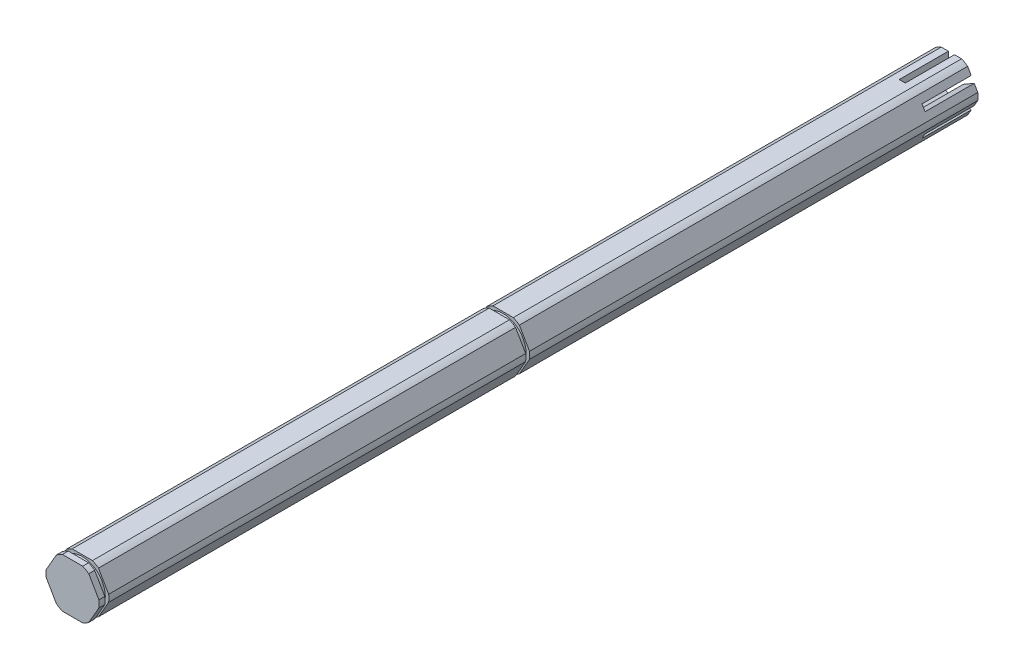
SolidWorks part; units mm, degrees
material "6061-T6 (SS)"
ref_plane "Front Plane" through (0, 0, 0) normal (0, 0, 1) x (1, 0, 0)
ref_plane "Top Plane" through (0, 0, 0) normal (0, 1, 0) x (1, 0, 0)
ref_plane "Right Plane" through (0, 0, 0) normal (1, 0, 0) x (0, 0, -1)
sketch "Sketch1" plane through (0, 0, 0) normal (1, 0, 0) x (0, 0, -1)
  line L0 (0, 0) -> (127, 0) construction
  line L1 (111.252, 7.62) -> (112.776, 7.62)
  line L2 (0, 0) -> (112.776, 0)
  line L3 (0, 0) -> (0, 7.62)
  line L4 (0, 7.62) -> (1.524, 7.62)
  line L5 (112.776, 0) -> (112.776, 7.62)
  line L7 (1.524, 7.62) -> (1.524, 5.9436)
  line L8 (1.524, 5.9436) -> (2.5146, 5.9436)
  line L9 (2.5146, 7.62) -> (2.5146, 5.9436)
  line L10 (110.2614, 5.9436) -> (111.252, 5.9436)
  line L11 (110.2614, 5.9436) -> (110.2614, 7.62)
  line L12 (2.5146, 7.62) -> (110.2614, 7.62)
  line L13 (111.252, 5.9436) -> (111.252, 7.62)
  dimension "D1" = 127
  dimension "D2" = 107.7468
  dimension "D3" = 7.62
  dimension "D4" = 0.9906
  dimension "D5" = 11.8872
  dimension "D6" = 1.524
  dimension "D8" = 1.524
revolve "Revolve3" add sketch "Sketch1" angle 360 about L0
sketch "Sketch2" plane through (0, 0, -112.776) normal (0, 0, -1) x (-1, 0, 0)
  line L1 (6.8111, 0.9028) -> (4.1874, 5.4472)
  line L2 (2.6237, 6.35) -> (-2.6237, 6.35)
  line L3 (-4.1874, 5.4472) -> (-6.8111, 0.9028)
  line L4 (-6.8111, -0.9028) -> (-4.1874, -5.4472)
  line L5 (-2.6237, -6.35) -> (2.6237, -6.35)
  line L6 (4.1874, -5.4472) -> (6.8111, -0.9028)
  circle A0 centre (0, 0) radius 6.35 construction
  arc A1 (-2.6237, 6.35) -> (-4.1874, 5.4472) centre (0, 0) ccw
  arc A2 (2.6237, -6.35) -> (4.1874, -5.4472) centre (0, 0) ccw
  arc A3 (-4.1874, -5.4472) -> (-2.6237, -6.35) centre (0, 0) ccw
  arc A4 (4.1874, 5.4472) -> (2.6237, 6.35) centre (0, 0) ccw
  arc A5 (6.8111, -0.9028) -> (6.8111, 0.9028) centre (0, 0) ccw
  arc A6 (-6.8111, 0.9028) -> (-6.8111, -0.9028) centre (0, 0) ccw
  dimension "D1" = 12.7
  dimension "D2" = 13.7414
extrude "Cut-Extrude1" cut sketch "Sketch2" against normal through all flip side to cut
sketch "Sketch3" plane through (0, 0, -112.776) normal (0, 0, -1) x (-1, 0, 0)
  line L6 (4.1874, -5.4472) -> (6.8111, -0.9028)
  line L7 (6.8111, 0.9028) -> (4.1874, 5.4472)
  line L8 (2.6237, 6.35) -> (-2.6237, 6.35)
  line L9 (-4.1874, 5.4472) -> (-6.8111, 0.9028)
  line L10 (-6.8111, -0.9028) -> (-4.1874, -5.4472)
  line L11 (-2.6237, -6.35) -> (2.6237, -6.35)
  line L12 (4.1874, -5.4472) -> (6.8111, -0.9028)
  line L13 (6.8111, 0.9028) -> (4.1874, 5.4472)
  line L14 (2.6237, 6.35) -> (-2.6237, 6.35)
  line L15 (-4.1874, 5.4472) -> (-6.8111, 0.9028)
  line L16 (-6.8111, -0.9028) -> (-4.1874, -5.4472)
  line L17 (-2.6237, -6.35) -> (2.6237, -6.35)
  circle A0 centre (0, 0) radius 2.4892
  arc A7 (2.6237, -6.35) -> (4.1874, -5.4472) centre (0, 0) ccw
  arc A8 (6.8111, -0.9028) -> (6.8111, 0.9028) centre (0, 0) ccw
  arc A9 (4.1874, 5.4472) -> (2.6237, 6.35) centre (0, 0) ccw
  arc A10 (-2.6237, 6.35) -> (-4.1874, 5.4472) centre (0, 0) ccw
  arc A11 (-6.8111, 0.9028) -> (-6.8111, -0.9028) centre (0, 0) ccw
  arc A12 (-4.1874, -5.4472) -> (-2.6237, -6.35) centre (0, 0) ccw
  arc A13 (2.6237, -6.35) -> (4.1874, -5.4472) centre (0, 0) ccw
  arc A14 (6.8111, -0.9028) -> (6.8111, 0.9028) centre (0, 0) ccw
  arc A15 (4.1874, 5.4472) -> (2.6237, 6.35) centre (0, 0) ccw
  arc A16 (-2.6237, 6.35) -> (-4.1874, 5.4472) centre (0, 0) ccw
  arc A17 (-6.8111, 0.9028) -> (-6.8111, -0.9028) centre (0, 0) ccw
  arc A18 (-4.1874, -5.4472) -> (-2.6237, -6.35) centre (0, 0) ccw
  dimension "D1" = 4.9784
  dimension "D2" = 0
extrude "Boss-Extrude1" add sketch "Sketch3" along normal blind 114.3
sketch "Sketch4" plane through (0, 0, -227.076) normal (0, 0, -1) x (-1, 0, 0)
  circle A0 centre (0, 0) radius 3.175
  dimension "D1" = 6.35
extrude "Cut-Extrude2" cut sketch "Sketch4" against normal blind 12.7
sketch "Sketch5" plane through (0, 0, -227.076) normal (0, 0, -1) x (-1, 0, 0)
  line L0 (-2.6237, -6.35) -> (2.6237, -6.35) construction
  line L1 (-0.7874, 6.35) -> (0.7874, 6.35)
  line L2 (-0.7874, 6.35) -> (-0.7874, -6.35)
  line L3 (-0.7874, -6.35) -> (0.7874, -6.35)
  line L4 (0.7874, 6.35) -> (0.7874, -6.35)
  line L5 (-0.7874, 6.35) -> (0.7874, -6.35) construction
  line L6 (-0.7874, -6.35) -> (0.7874, 6.35) construction
  point P0 (0, 0)
  dimension "D1" = 1.5748
extrude "Cut-Extrude3" cut sketch "Sketch5" against normal blind 12.7
pattern_circular "CirPattern1" count 6 over 360 about axis through (0, 0, 0) along (0, 0, 1) of "Cut-Extrude3"
